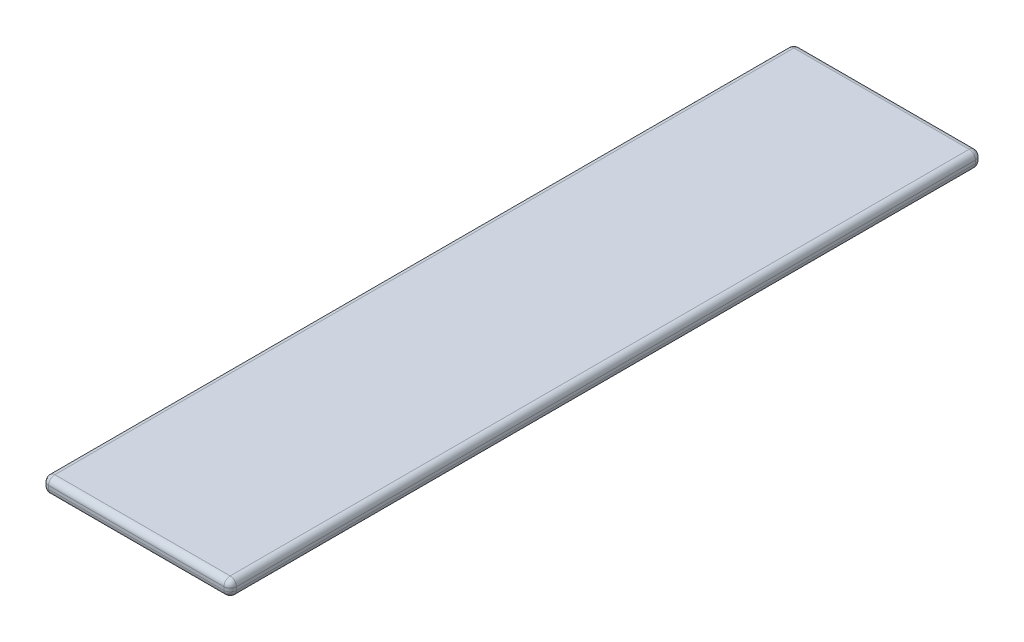
SolidWorks part; units mm, degrees
material "Balsa"
ref_plane "Front" through (0, 0, 0) normal (0, 0, 1) x (1, 0, 0)
ref_plane "Top" through (0, 0, 0) normal (0, 1, 0) x (1, 0, 0)
ref_plane "Right" through (0, 0, 0) normal (1, 0, 0) x (0, 0, -1)
sketch "Sketch1" plane through (0, 0, 0) normal (0, 0, 1) x (1, 0, 0)
  line L1 (0, 0) -> (-254, 0)
  line L2 (0, 0) -> (0, 6.35)
  line L3 (0, 6.35) -> (-254, 6.35)
  line L4 (-254, 0) -> (-254, 6.35)
  dimension "D1" = 6.35
  dimension "D2" = 254
extrude "Boss-Extrude1" add sketch "Sketch1" along normal blind 304.8 contours L3 L4 L1 L2
sketch "Sketch2" plane through (0, 6.35, 0) normal (0, 1, 0) x (1, 0, 0)
  line L0 (-254, 0) -> (-101.6, -304.8)
  line L1 (0, -304.8) -> (-254, -304.8) construction
  line L2 (0, -304.8) -> (-254, -304.8)
  line L3 (0, -304.8) -> (-254, -304.8)
  line L4 (-254, -304.8) -> (-254, 0)
  line L5 (-254, -304.8) -> (-254, 0)
  line L6 (-254, 0) -> (0, 0)
  line L7 (-254, 0) -> (0, 0)
  line L8 (0, 0) -> (0, -304.8)
  line L9 (0, 0) -> (0, -304.8)
  line M2 (-254, 0) -> (-254, -304.8)
  line M3 (-254, -304.8) -> (0, -304.8)
  dimension "D1" = 101.6
extrude "Cut-Extrude1" cut sketch "Sketch2" against normal blind 304.8 contours L0 M2 M3
sketch "Sketch4" plane through (0, 6.35, 0) normal (0, 1, 0) x (1, 0, 0)
  line L0 (0, -304.8) -> (-101.6, -304.8) construction
  line L1 (-76.2, 35.4703) -> (-257.808, 35.4703)
  line L2 (-76.2, 35.4703) -> (-76.2, -363.5801)
  line L3 (-76.2, -363.5801) -> (-257.808, -363.5801)
  line L4 (-257.808, 35.4703) -> (-257.808, -363.5801)
  line L6 (-76.2, -304.8) -> (-76.2, -234.95)
  line L9 (-254, 0) -> (-101.6, -304.8) construction
  line L10 (0, 0) -> (-244.4345, 0)
  line L11 (0, 0) -> (0, -19.05)
  line L13 (-244.4345, 0) -> (-244.4345, -19.1311)
  line M2 (-254, 0) -> (-101.6, -304.8)
  line M3 (-101.6, -304.8) -> (0, -304.8)
  line M5 (0, 0) -> (-254, 0)
  dimension "D1" = 25.4
extrude "Cut-Extrude2" cut sketch "Sketch4" against normal through all contours L1 L4 L3 L2 M3 M2 M5
fillet "Fillet2" radius 2.54 12 edges at (0, 3.175, 304.8) (0, 6.35, 152.4) (0, 0, 152.4) (-38.1, 6.35, 304.8) (-38.1, 0, 304.8) (-76.2, 0, 152.4) (-76.2, 6.35, 152.4) (-38.1, 6.35, 0) (-76.2, 3.175, 0) (-38.1, 0, 0) (0, 3.175, 0) (-76.2, 3.175, 304.8)
sketch "Sketch7" plane through (0, 6.35, 0) normal (0, 1, 0) x (1, 0, 0)
  line L5 (-76.2, 0) -> (-76.2, -304.8) construction
  line L6 (-76.2, -234.95) -> (-68.58, -234.95)
  line L7 (-76.2, -234.95) -> (-76.2, -203.2)
  line L8 (-76.2, -203.2) -> (-68.58, -203.2)
  line L9 (-68.58, -234.95) -> (-68.58, -203.2)
  line L11 (-76.2, -69.85) -> (-68.58, -69.85)
  line L12 (-76.2, -69.85) -> (-76.2, -101.6)
  line L13 (-76.2, -101.6) -> (-68.58, -101.6)
  line L14 (-68.58, -69.85) -> (-68.58, -101.6)
  line L15 (-76.2, -304.8) -> (-68.58, -304.8)
  line L16 (-76.2, -304.8) -> (-76.2, -285.75)
  line L17 (-76.2, -285.75) -> (-68.58, -285.75)
  line L18 (-68.58, -304.8) -> (-68.58, -285.75)
  line L19 (-73.66, 0) -> (-2.54, 0) construction
  dimension "D1" = 31.75
  dimension "D2" = 31.75
  dimension "D3" = 69.85
  dimension "D4" = 69.85
  dimension "D5" = 7.62
  dimension "D6" = 19.05
extrude "Cut-Extrude3" [suppressed] cut sketch "Sketch7" against normal through all contours L6 L9 L8 L7 | L15 L18 L17 L16 | L13 L14 L11 L12
